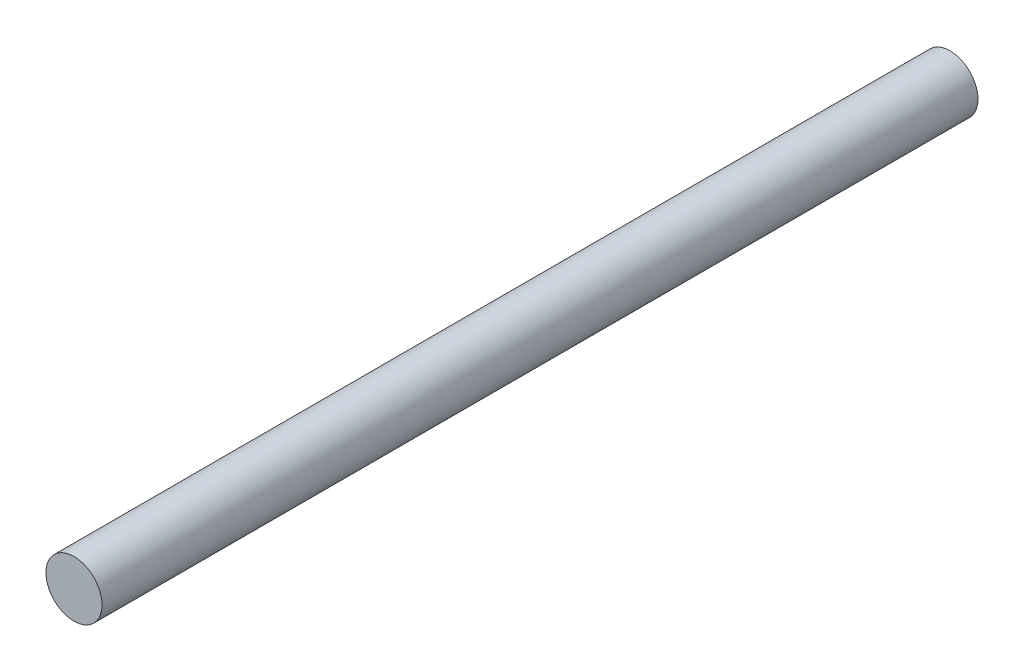
SolidWorks part; units mm, degrees
ref_plane "Płaszczyzna przednia" through (0, 0, 0) normal (0, 0, 1) x (1, 0, 0)
ref_plane "Płaszczyzna górna" through (0, 0, 0) normal (0, 1, 0) x (1, 0, 0)
ref_plane "Płaszczyzna prawa" through (0, 0, 0) normal (1, 0, 0) x (0, 0, -1)
sketch "Szkic1" plane through (0, 0, 0) normal (0, 0, 1) x (1, 0, 0)
  circle A0 centre (0, 0) radius 16
  dimension "D1" = 32
extrude "Dodanie-wyciągnięcie1" add sketch "Szkic1" along normal blind 500
